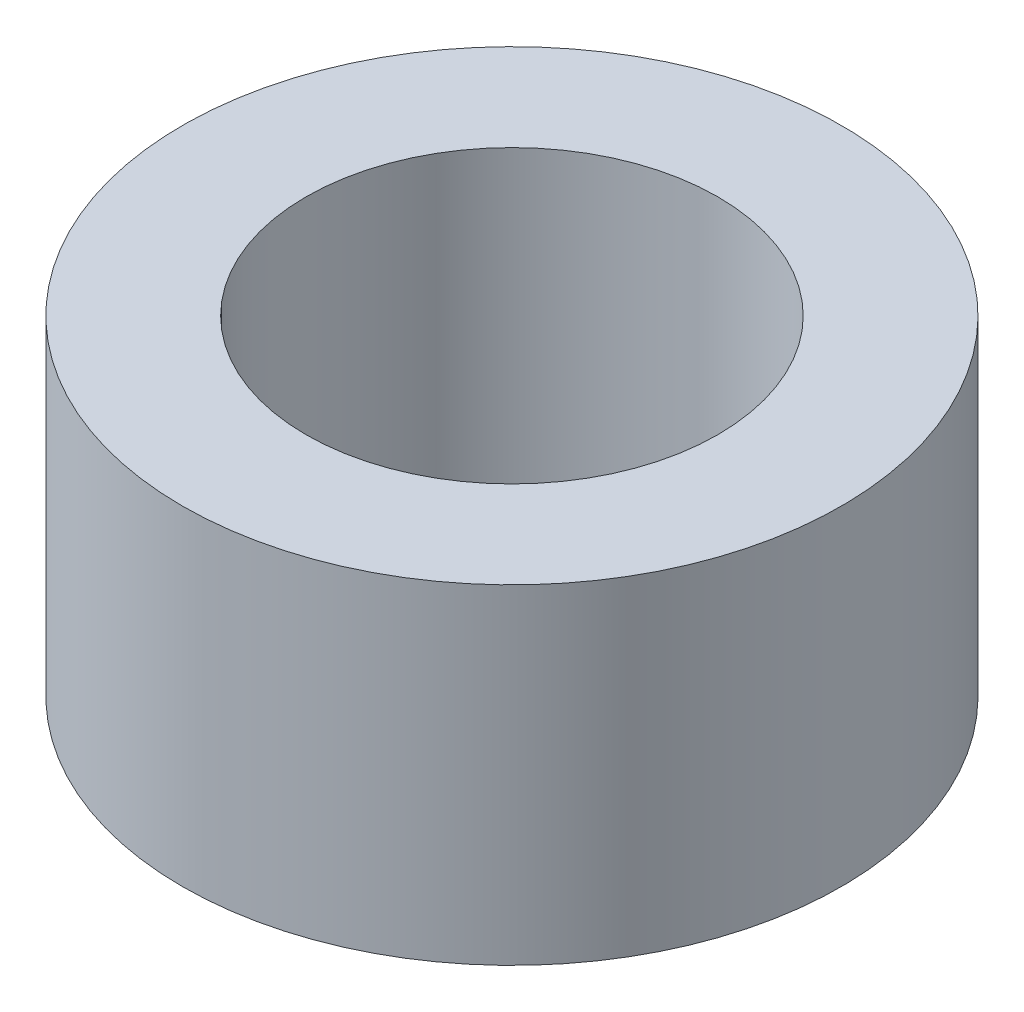
SolidWorks part; units mm, degrees
ref_plane "Front Plane" through (0, 0, 0) normal (0, 0, 1) x (1, 0, 0)
ref_plane "Top Plane" through (0, 0, 0) normal (0, 1, 0) x (1, 0, 0)
ref_plane "Right Plane" through (0, 0, 0) normal (1, 0, 0) x (0, 0, -1)
sketch "Sketch1" plane through (0, 0, 0) normal (0, 1, 0) x (1, 0, 0)
  circle A0 centre (0, 0) radius 5
  circle A1 centre (0, 0) radius 3.125
  dimension "D1" = 10
  dimension "D2" = 6.25
extrude "Boss-Extrude1" add sketch "Sketch1" along normal mid plane 5
